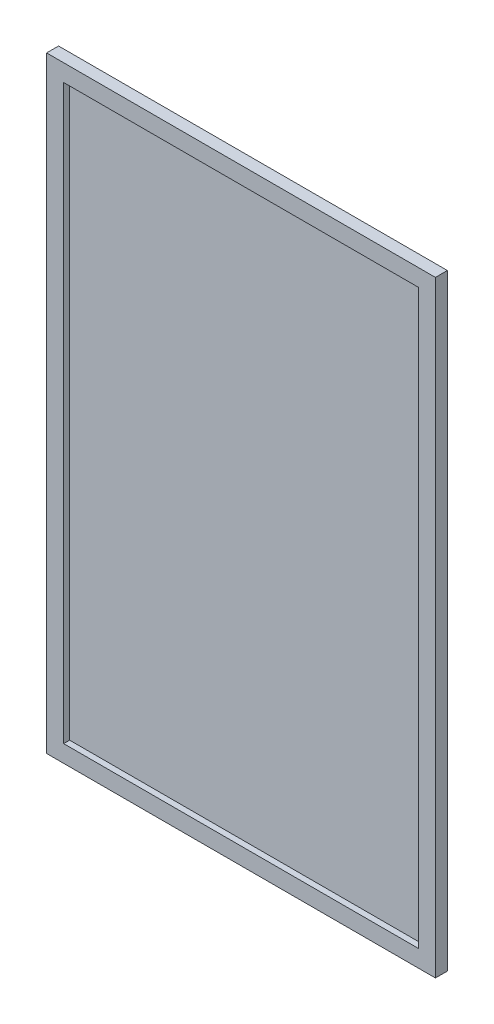
SolidWorks part; units mm, degrees
ref_plane "Front Plane" through (0, 0, 0) normal (0, 0, 1) x (1, 0, 0)
ref_plane "Top Plane" through (0, 0, 0) normal (0, 1, 0) x (1, 0, 0)
ref_plane "Right Plane" through (0, 0, 0) normal (1, 0, 0) x (0, 0, -1)
sketch "Sketch1" plane through (0, 0, 0) normal (0, 0, 1) x (1, 0, 0)
  line L1 (0, 0) -> (2311.4, 0)
  line L2 (0, 0) -> (0, 3606.8)
  line L3 (0, 3606.8) -> (2311.4, 3606.8)
  line L4 (2311.4, 0) -> (2311.4, 3606.8)
  line L5 (0, 0) -> (2311.4, 3606.8) construction
  line L6 (0, 3606.8) -> (2311.4, 0) construction
  point P4 (1155.7, 1803.4)
  dimension "D1" = 2311.4
  dimension "D2" = 3606.8
extrude "Boss-Extrude1" add sketch "Sketch1" along normal blind 71.12
sketch "Sketch2" plane through (0, 0, 71.12) normal (0, 0, 1) x (1, 0, 0)
  line L0 (2311.4, 0) -> (2311.4, 3606.8) construction
  line L1 (101.6, 101.6) -> (2209.8, 101.6)
  line L2 (101.6, 101.6) -> (101.6, 3505.2)
  line L3 (101.6, 3505.2) -> (2209.8, 3505.2)
  line L4 (2209.8, 101.6) -> (2209.8, 3505.2)
  line L5 (101.6, 101.6) -> (2209.8, 3505.2) construction
  line L6 (101.6, 3505.2) -> (2209.8, 101.6) construction
  line L7 (2311.4, 3606.8) -> (0, 3606.8) construction
  line L8 (0, 3606.8) -> (0, 0) construction
  line L9 (0, 0) -> (2311.4, 0) construction
  point P4 (1155.7, 1803.4)
  dimension "D1" = 101.6
  dimension "D2" = 101.6
  dimension "D3" = 101.6
  dimension "D4" = 101.6
extrude "Cut-Extrude1" cut sketch "Sketch2" against normal blind 35.56
